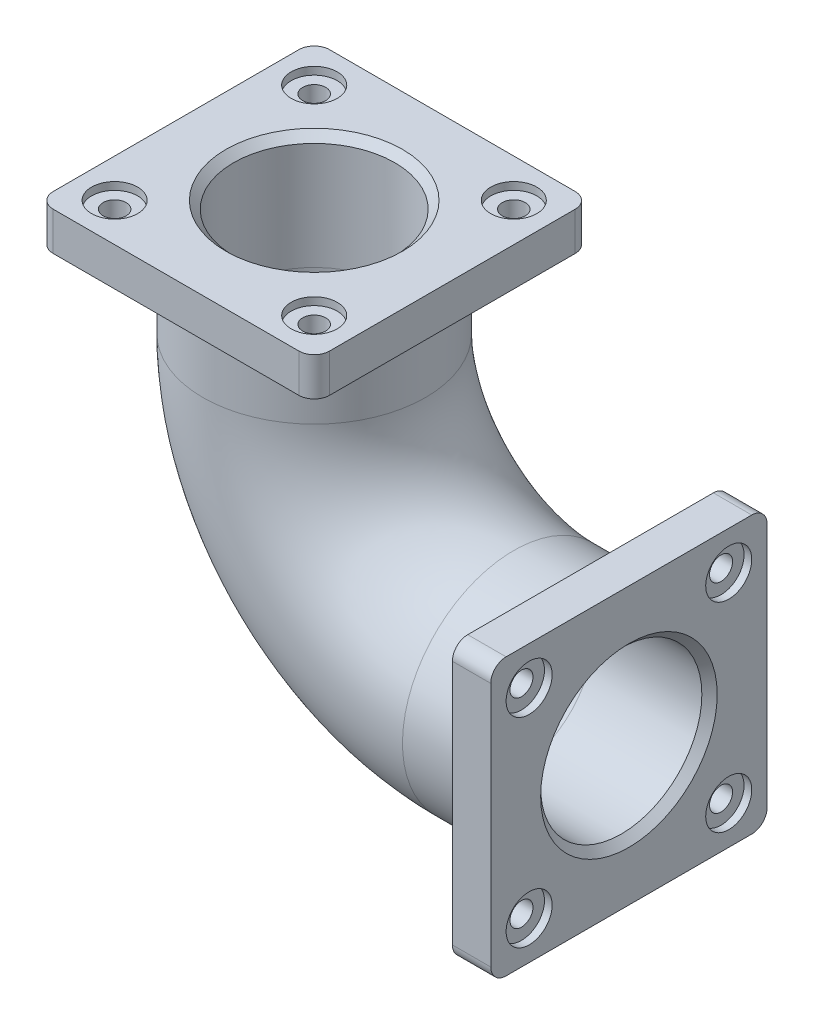
SolidWorks part; units mm, degrees
ref_plane "Front Plane" through (0, 0, 0) normal (0, 0, 1) x (1, 0, 0)
ref_plane "Top Plane" through (0, 0, 0) normal (0, 1, 0) x (1, 0, 0)
ref_plane "Right Plane" through (0, 0, 0) normal (1, 0, 0) x (0, 0, -1)
sketch "Sketch1" plane through (0, 0, 0) normal (0, 0, 1) x (1, 0, 0)
  line L0 (0, 0) -> (-150, 0)
  line L1 (-410, 260) -> (-410, 410)
  arc A0 (-150, 0) -> (-410, 260) centre (-150, 260) cw
  dimension "D2" = 260
  dimension "D1" = 150
sketch "Sketch2" plane through (0, 0, 0) normal (1, 0, 0) x (0, 0, -1)
  circle A0 centre (0, 0) radius 145
  dimension "D1" = 290
sweep "Sweep-Thin1" add profiles "Sketch2" path "Sketch1" parameters "D1"=40
sketch "Sketch3" plane through (0, 0, 0) normal (1, 0, 0) x (0, 0, -1)
  line L1 (-180, 180) -> (180, 180)
  line L2 (-180, 180) -> (-180, -180)
  line L3 (-180, -180) -> (180, -180)
  line L4 (180, 180) -> (180, -180)
  line L5 (-180, 180) -> (180, -180) construction
  line L6 (-180, -180) -> (180, 180) construction
  point P0 (0, 0)
  circle M5 centre (0, 0) radius 145
  dimension "D1" = 360
  dimension "D2" = 360
extrude "Boss-Extrude1" add sketch "Sketch3" against normal blind 50 contours L4 L1 L2 L3 M5
fillet "Fillet1" radius 20 4 edges at (-25, 180, -180) (-25, -180, 180) (-25, -180, -180) (-25, 180, 180)
sketch "Sketch4" plane through (0, 410, 0) normal (0, 1, 0) x (1, 0, 0)
  line L1 (-570, 180) -> (-250, 180)
  line L2 (-590, 160) -> (-590, -160)
  line L3 (-570, -180) -> (-250, -180)
  line L4 (-230, 160) -> (-230, -160)
  line L5 (-590, 180) -> (-230, -180) construction
  line L6 (-590, -180) -> (-230, 180) construction
  arc A0 (-590, -160) -> (-570, -180) centre (-570, -160) ccw
  arc A1 (-250, -180) -> (-230, -160) centre (-250, -160) ccw
  arc A2 (-250, 180) -> (-230, 160) centre (-250, 160) cw
  arc A3 (-570, 180) -> (-590, 160) centre (-570, 160) ccw
  point P0 (-410, 0)
  circle M4 centre (-410, 0) radius 145
  dimension "D3" = 20
  dimension "D1" = 360
  dimension "D2" = 360
extrude "Boss-Extrude2" add sketch "Sketch4" against normal blind 50 contours L1 A3 L2 A0 L3 A1 L4 A2 M4
sketch "Sketch5" plane through (0, 0, 0) normal (1, 0, 0) x (0, 0, -1)
  line L1 (-130, 130) -> (130, 130) construction
  line L2 (-130, 130) -> (-130, -130) construction
  line L3 (-130, -130) -> (130, -130) construction
  line L4 (130, 130) -> (130, -130) construction
  line L5 (-130, 130) -> (130, -130) construction
  line L6 (-130, -130) -> (130, 130) construction
  circle A0 centre (-130, 130) radius 30
  point P0 (0, 0)
  dimension "D3" = 60
  dimension "D1" = 260
  dimension "D2" = 260
extrude "Cut-Extrude1" cut sketch "Sketch5" against normal blind 10
sketch "Sketch6" plane through (-10, 0, 0) normal (1, 0, 0) x (0, 0, -1)
  circle A0 centre (-130, 130) radius 15
  dimension "D1" = 30
extrude "Cut-Extrude2" cut sketch "Sketch6" against normal blind 86
sketch "Sketch7" plane through (0, 0, 0) normal (0, 0, 1) x (1, 0, 0)
  line L0 (211.28, 0) -> (-539.7332, 0) construction
  line L1 (-410, 410) -> (-410, -164.4974) construction
  line L2 (-570, 410) -> (-250, 410) construction
pattern_circular "CirPattern1" count 4 over 360 about axis through (0, 0, 0) along (1, 0, 0) of "Cut-Extrude1", "Cut-Extrude2"
sketch "Sketch9" plane through (0, 410, 0) normal (0, 1, 0) x (1, 0, 0)
  line L1 (-540, 130) -> (-280, 130) construction
  line L2 (-540, 130) -> (-540, -130) construction
  line L3 (-540, -130) -> (-280, -130) construction
  line L4 (-280, 130) -> (-280, -130) construction
  line L5 (-540, 130) -> (-280, -130) construction
  line L6 (-540, -130) -> (-280, 130) construction
  circle A0 centre (-540, 130) radius 30
  point P0 (-410, 0)
  dimension "D1" = 60
  dimension "D2" = 260
  dimension "D3" = 260
extrude "Cut-Extrude3" cut sketch "Sketch9" against normal blind 10
sketch "Sketch10" plane through (0, 400, 0) normal (0, 1, 0) x (1, 0, 0)
  circle A0 centre (-540, 130) radius 15
  dimension "D1" = 30
extrude "Cut-Extrude4" cut sketch "Sketch10" against normal up to next
pattern_circular "CirPattern2" count 4 over 360 about axis through (-410, 0, 0) along (0, 1, 0) of "Cut-Extrude4", "Cut-Extrude3"
chamfer "Chamfer1" distance 10 angle 45 2 edges at (-410, 410, -105) (0, 0, -105)
